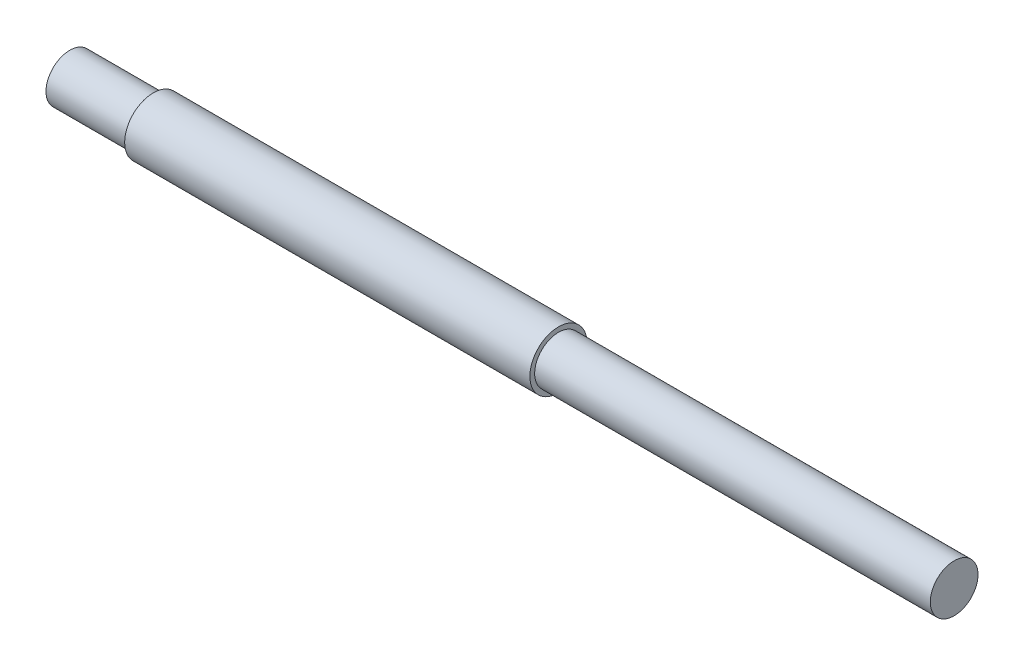
SolidWorks part; units mm, degrees
ref_plane "Plan de face" through (0, 0, 0) normal (0, 0, 1) x (1, 0, 0)
ref_plane "Plan de dessus" through (0, 0, 0) normal (0, 1, 0) x (1, 0, 0)
ref_plane "Plan de droite" through (0, 0, 0) normal (1, 0, 0) x (0, 0, -1)
sketch "Esquisse2" plane through (0, 0, 0) normal (0, 1, 0) x (1, 0, 0)
  line L0 (0, 0) -> (185.5, 0)
  line L1 (0, 0) -> (0, 6)
  line L2 (0, 6) -> (185.5, 6)
  line L3 (185.5, 6) -> (185.5, 0)
  dimension "D1" = 185.5
  dimension "D2" = 6
revolve "Révolution2" add sketch "Esquisse2" angle 360 about L2
sketch "Esquisse3" plane through (185.5, 0, 0) normal (1, 0, 0) x (0, 0, -1)
  line L0 (12, 0) -> (0, 0) construction
  circle A0 centre (6, 0) radius 6 construction
  circle A1 centre (6, 0) radius 5
  circle A2 centre (6, 0) radius 6
  dimension "D1" = 10
extrude "Enlèv. mat.-Extru.1" cut sketch "Esquisse3" against normal blind 83
sketch "Esquisse5" plane through (0, 0, 0) normal (-1, 0, 0) x (0, 0, 1)
  line L0 (-12, 0) -> (0, 0)
  circle A0 centre (-6, 0) radius 6 construction
  circle A1 centre (-6, 0) radius 5
  circle M1 centre (-6, 0) radius 6
extrude "Enlèv. mat.-Extru.2" cut sketch "Esquisse5" against normal blind 17.5 contours A1 L0 M1 | A1 L0 M1
